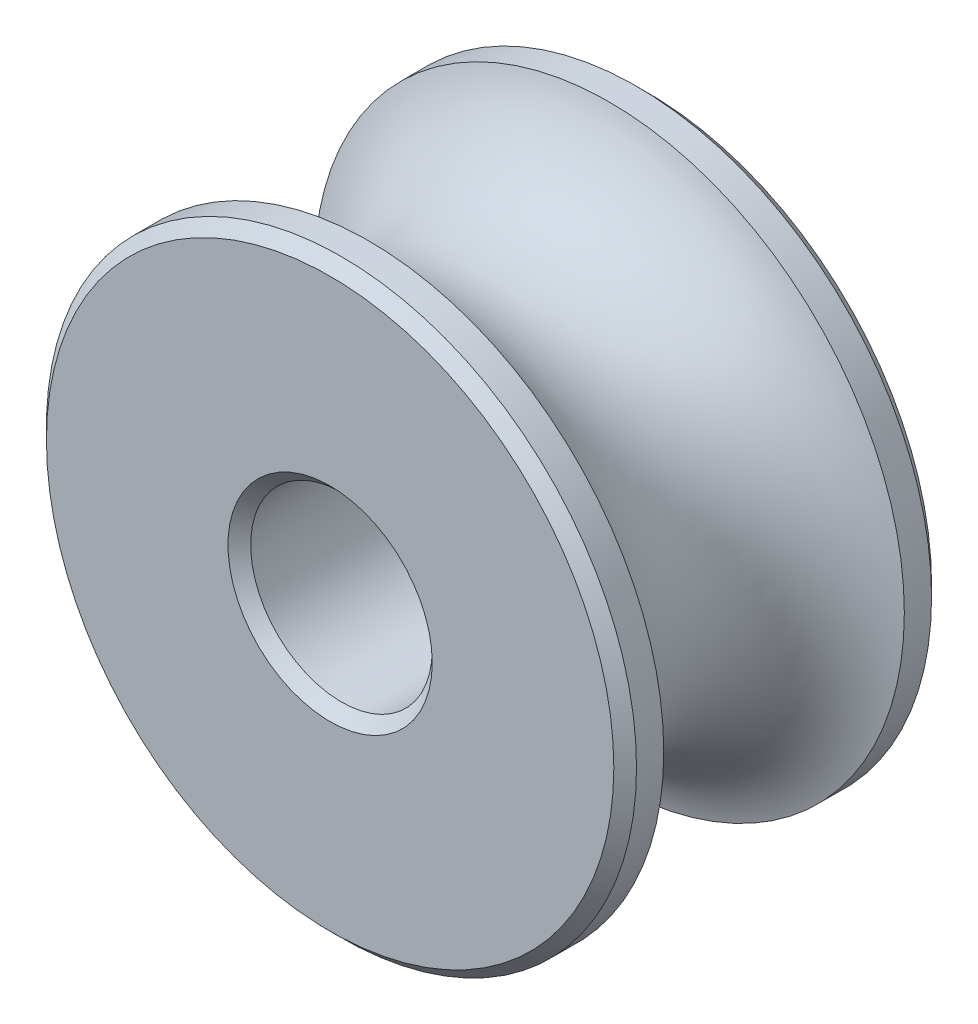
SolidWorks part; units mm, degrees
ref_plane "Front Plane" through (0, 0, 0) normal (0, 0, 1) x (1, 0, 0)
ref_plane "Top Plane" through (0, 0, 0) normal (0, 1, 0) x (1, 0, 0)
ref_plane "Right Plane" through (0, 0, 0) normal (1, 0, 0) x (0, 0, -1)
ref_plane "Plane1" through (0, 28.5749, 0) normal (0, 1, 0) x (1, 0, 0)
sketch "Sketch1" plane through (0, 28.5749, 0) normal (0, 1, 0) x (1, 0, 0)
  line L0 (-120.6816, -17.71) -> (-120.9316, -17.46)
  line L1 (-120.9316, -17.46) -> (-124.9316, -17.46)
  line L2 (-124.9316, -17.46) -> (-125.1816, -17.71)
  line L3 (-125.1816, -17.71) -> (-125.1816, -24.21)
  line L4 (-125.1816, -24.21) -> (-124.9316, -24.46)
  line L5 (-124.9316, -24.46) -> (-120.9316, -24.46)
  line L6 (-120.9316, -24.46) -> (-120.6816, -24.21)
  line L7 (-120.6816, -24.21) -> (-120.6816, -23.61)
  line L8 (-120.6816, -18.31) -> (-120.6816, -17.71)
  line L9 (-127.1816, -17.46) -> (-127.1816, -24.46) construction
  arc A0 (-120.6816, -23.61) -> (-120.6816, -18.31) centre (-119.926, -20.96) cw
revolve "Revolve1" add sketch "Sketch1" angle 360 about L9
